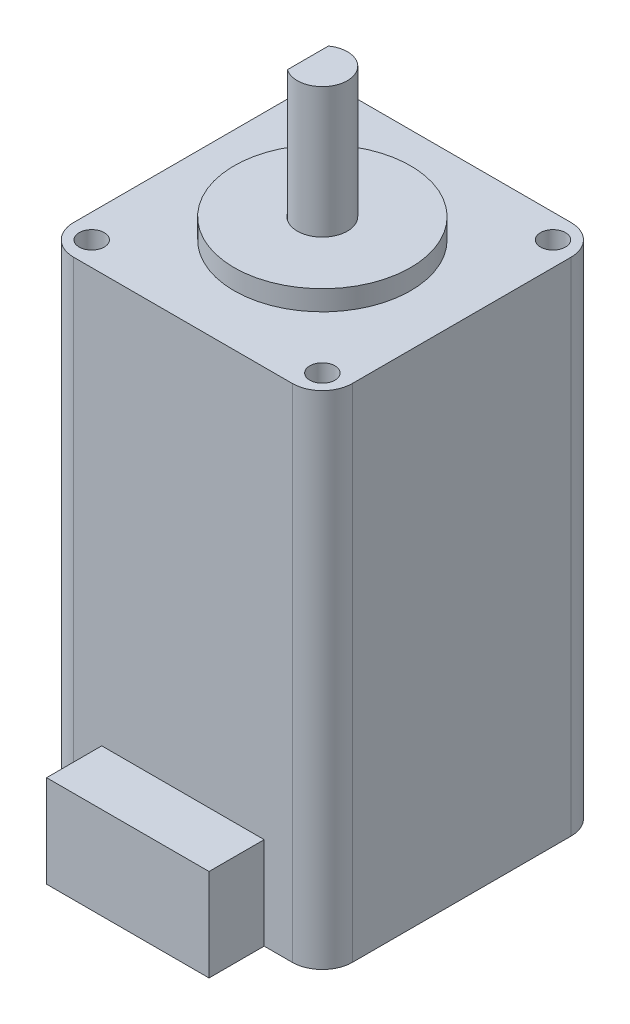
SolidWorks part; units mm, degrees
ref_plane "前视基准面" through (0, 0, 0) normal (0, 0, 1) x (1, 0, 0)
ref_plane "上视基准面" through (0, 0, 0) normal (0, 1, 0) x (1, 0, 0)
ref_plane "右视基准面" through (0, 0, 0) normal (1, 0, 0) x (0, 0, -1)
sketch "草图1" plane through (0, 0, 0) normal (0, 1, 0) x (1, 0, 0)
  line L1 (-13.9, 13.9) -> (13.9, 13.9)
  line L2 (-13.9, 13.9) -> (-13.9, -13.9)
  line L3 (-13.9, -13.9) -> (13.9, -13.9)
  line L4 (13.9, 13.9) -> (13.9, -13.9)
  line L5 (-13.9, 13.9) -> (13.9, -13.9) construction
  line L6 (-13.9, -13.9) -> (13.9, 13.9) construction
  point P0 (0, 0)
  dimension "D1" = 27.8
extrude "凸台-拉伸1" add sketch "草图1" along normal blind 50
sketch "草图2" plane through (0, 50, 0) normal (0, 1, 0) x (1, 0, 0)
  circle A0 centre (0, 0) radius 8.8
  dimension "D1" = 17.6
extrude "凸台-拉伸2" add sketch "草图2" along normal blind 2
sketch "草图3" plane through (0, 52, 0) normal (0, 1, 0) x (1, 0, 0)
  circle A0 centre (0, 0) radius 2.5
  dimension "D1" = 5
extrude "凸台-拉伸3" add sketch "草图3" along normal blind 13
sketch "草图5" plane through (0, 0, 13.9) normal (0, 0, 1) x (1, 0, 0)
  line L0 (-13.9, 0) -> (13.9, 0) construction
  line L1 (-8.1, 9.2) -> (8.1, 9.2)
  line L2 (-8.1, 9.2) -> (-8.1, 0)
  line L3 (-8.1, 0) -> (8.1, 0)
  line L4 (8.1, 9.2) -> (8.1, 0)
  line L5 (-8.1, 9.2) -> (8.1, 0) construction
  line L6 (-8.1, 0) -> (8.1, 9.2) construction
  point P0 (0, 4.6)
  dimension "D1" = 9.2
  dimension "D2" = 16.2
extrude "凸台-拉伸4" add sketch "草图5" along normal blind 5.5
sketch "草图6" plane through (0, 50, 0) normal (0, 1, 0) x (1, 0, 0)
  line L0 (-13.9, 13.9) -> (13.9, -13.9) construction
  line L1 (13.9, 13.9) -> (-13.9, -13.9) construction
  line L2 (0, 0) -> (40.1341, 0) construction
  circle A0 centre (-11.5, 11.5) radius 1.25
  circle A2 centre (11.5, 11.5) radius 1.25
  circle A3 centre (11.5, -11.5) radius 1.25
  circle A4 centre (-11.5, -11.5) radius 1.25
  point P23 (0, 0)
  dimension "D1" = 2.5
  dimension "D2" = 23
  dimension "D3" = 4
extrude "切除-拉伸1" cut sketch "草图6" against normal blind 5
fillet "圆角1" radius 3 4 edges at (13.9, 25, -13.9) (-13.9, 25, -13.9) (13.9, 25, 13.9) (-13.9, 25, 13.9)
sketch "草图7" plane through (0, 0, 0) normal (0, -1, 0) x (1, 0, 0)
  circle A0 centre (0, 0) radius 4
  dimension "D1" = 8
extrude "切除-拉伸2" cut sketch "草图7" against normal blind 5
sketch "草图8" plane through (0, 65, 0) normal (0, 1, 0) x (1, 0, 0)
  line L0 (-1.4382, 2.0449) -> (-1.4382, -2.0449)
  circle A0 centre (0, 0) radius 2.5 construction
  circle A1 centre (0, 0) radius 2.5 construction
  circle A2 centre (0, 0) radius 2.5
  circle M2 centre (0, 0) radius 2.5
extrude "切除-拉伸3" cut sketch "草图8" against normal blind 20 contours L0 M2
